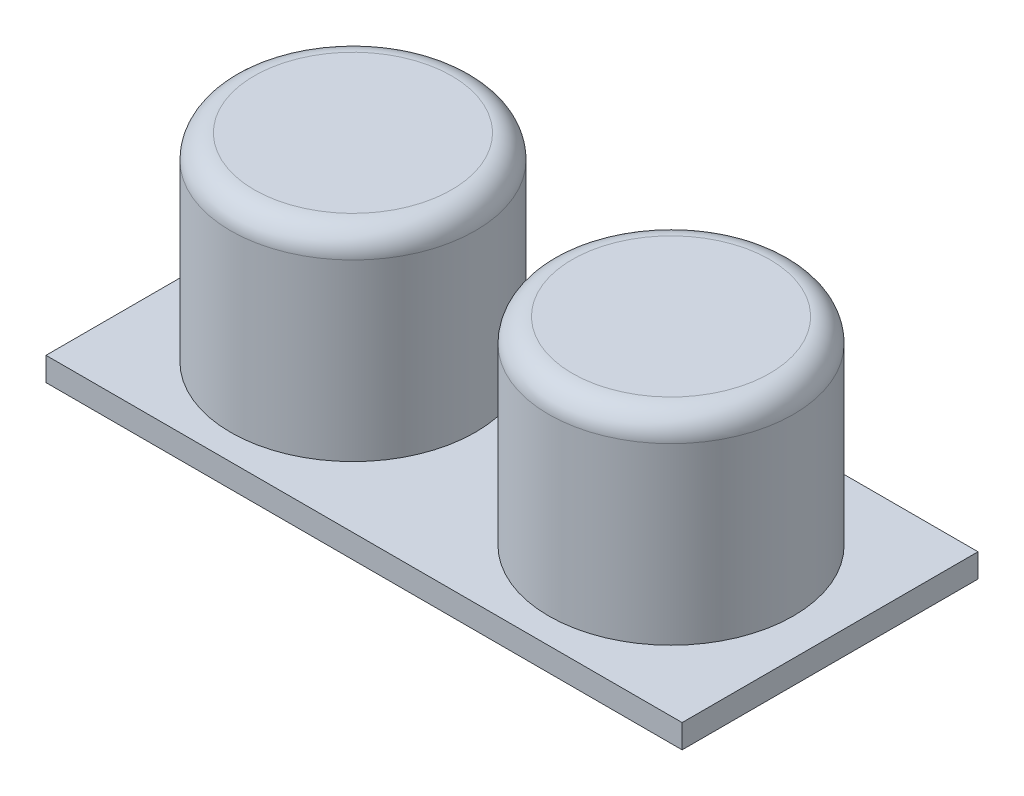
SolidWorks part; units mm, degrees
ref_plane "정면" through (0, 0, 0) normal (0, 0, 1) x (1, 0, 0)
ref_plane "윗면" through (0, 0, 0) normal (0, 1, 0) x (1, 0, 0)
ref_plane "우측면" through (0, 0, 0) normal (1, 0, 0) x (0, 0, -1)
sketch "스케치1" plane through (0, 0, 0) normal (0, 1, 0) x (1, 0, 0)
  line L0 (-26.9664, 0) -> (24.8538, 0)
  line L1 (0, 21.946) -> (0, -23.4566)
  line L3 (21.5, -10) -> (-21.5, -10)
  line L4 (21.5, -10) -> (21.5, 10)
  line L5 (21.5, 10) -> (-21.5, 10)
  line L6 (-21.5, -10) -> (-21.5, 10)
  line L7 (21.5, -10) -> (-21.5, 10) construction
  line L8 (21.5, 10) -> (-21.5, -10) construction
  point P8 (0, 0)
  dimension "D1" = 43
  dimension "D2" = 20
extrude "보스-돌출1" add sketch "스케치1" along normal blind 1.6 contours L4 L5 L6 L3
sketch "스케치2" plane through (0, 1.6, 0) normal (0, 1, 0) x (1, 0, 0)
  line L0 (0, 0) -> (27.724, 0) construction
  line L1 (27.724, 0) -> (-33.3658, 0) construction
  line L2 (0, 0) -> (0, 17.8068) construction
  line L3 (0, 17.8068) -> (0, -18.7324) construction
  line L4 (-10.75, 17.8068) -> (-10.75, -18.7324) construction
  circle A0 centre (-10.75, 0) radius 8.2729
  circle A1 centre (10.75, 0) radius 8.2729
  point P10 (-10.75, 0)
  point P11 (-10.75, 0)
  dimension "D1" = 10.75
extrude "보스-돌출2" add sketch "스케치2" along normal blind 13.4
fillet "필렛1" radius 1.6 2 edges at (-10.75, 15, 8.2729) (10.75, 15, -8.2729)
sketch "스케치9" plane through (0, 0, 0) normal (0, -1, 0) x (1, 0, 0)
  line L0 (-28.3411, 0) -> (26.2695, 0) construction
  line L1 (0, 0) -> (0, 18.0272) construction
  line L2 (0, 18.0272) -> (0, -15.9556) construction
  line L3 (-1.27, 18.0272) -> (-1.27, -15.6912) construction
  line L4 (-3.81, 18.2035) -> (-3.81, -15.5149) construction
  line L5 (-27.2832, -8.3) -> (27.3273, -8.3) construction
  line L15 (21.5, -10) -> (-21.5, -10) construction
  line L16 (3.81, -9.8649) -> (-6.35, -9.8649)
  line L17 (3.81, -9.8649) -> (3.81, -7.3249)
  line L18 (3.81, -7.3249) -> (-6.35, -7.3249)
  line L19 (-6.35, -9.8649) -> (-6.35, -7.3249)
  line L20 (3.81, -9.8649) -> (-6.35, -7.3249) construction
  line L21 (3.81, -7.3249) -> (-6.35, -9.8649) construction
  line L22 (-27.2832, -8.3) -> (27.3273, -8.3) construction
  point P12 (-1.27, -8.5949)
  point P15 (-1.27, -8.5949)
  dimension "D1" = 2.54
  dimension "D2" = 1.27
  dimension "D3" = 10.16
  dimension "D4" = 2.54
  dimension "D5" = 1.7
extrude "보스-돌출3" add sketch "스케치9" along normal blind 1.6 contours L16 L19 L18 L17
sketch "스케치20" plane through (0, 0, -9.8649) normal (0, 0, -1) x (-1, 0, 0)
  line L0 (0, -11.2203) -> (0, 25.9935) construction
  line L1 (-26.5486, -5.9106) -> (33.0027, -5.9106) construction
  line L2 (33.0027, -8.1993) -> (-26.5486, -8.1993) construction
  line L3 (-27.4641, -4.5374) -> (32.0872, -4.5374) construction
